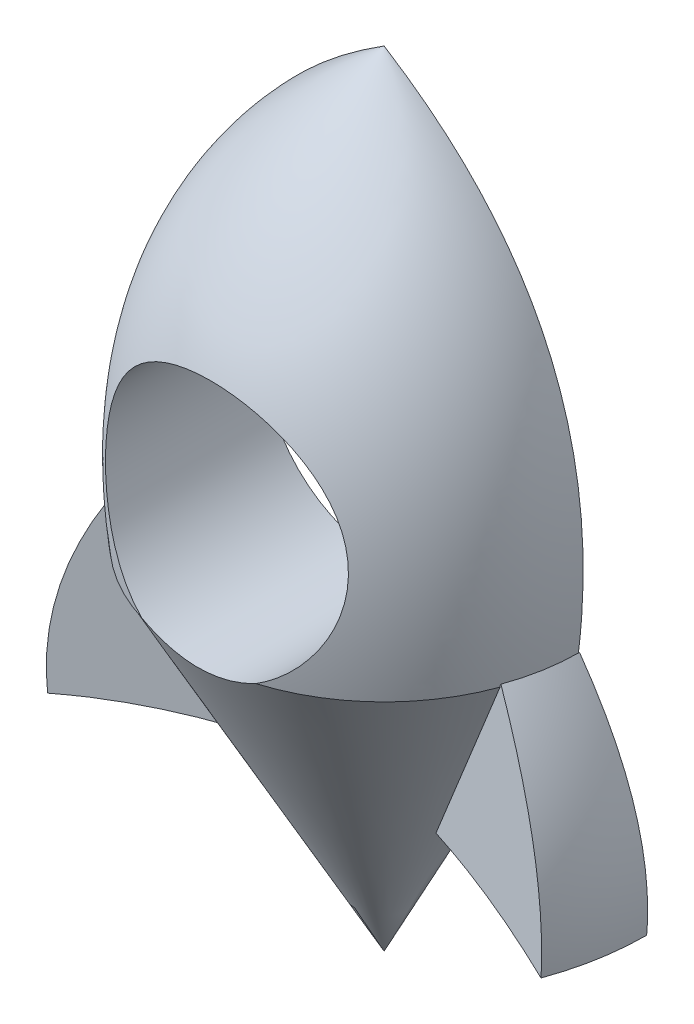
SolidWorks part; units mm, degrees
ref_plane "Front Plane" through (0, 0, 0) normal (0, 0, 1) x (1, 0, 0)
ref_plane "Top Plane" through (0, 0, 0) normal (0, 1, 0) x (1, 0, 0)
ref_plane "Right Plane" through (0, 0, 0) normal (1, 0, 0) x (0, 0, -1)
sketch "Sketch1" plane through (0, 0, 0) normal (0, 0, 1) x (1, 0, 0)
  line L0 (41.2575, 134.337) -> (163.2575, 134.337) construction
  line L1 (37.0343, 1.5646) -> (18.4311, 35.4141)
  line L4 (37.0343, 1.5646) -> (37.0343, 34.0429)
  line L5 (37.0343, 57.2579) -> (37.0343, 76.7324)
  arc A0 (37.0343, 57.2579) -> (37.0343, 34.0429) centre (37.0343, 45.6504) ccw
  spline S0 degree 2 poles (18.4311, 35.4141) (14.8948, 62.9056) (37.0343, 76.7324) knots 0 0 0 1 1 1
revolve "Revolve1" add sketch "Sketch1" angle 180 about L5
sketch "Sketch2" plane through (0, 0, 0) normal (0, 0, -1) x (-1, 0, 0)
  circle A0 centre (-37.0343, 45.6504) radius 11.6075
extrude "Cut-Extrude1" cut sketch "Sketch2" against normal blind 30
sketch "Sketch3" plane through (0, 0, 0) normal (0, 0, -1) x (-1, 0, 0)
  line L0 (-55.7749, 35.7487) -> (-45.3066, 16.701)
  line L1 (-37.0343, 76.7324) -> (-37.0343, 1.5646) construction
  line L2 (-18.2936, 35.7487) -> (-28.762, 16.701)
  spline S0 degree 2 poles (-45.3066, 16.701) (-54.0698, 17.2628) (-62.2069, 15.4708) knots 0 0 0 0.385925 0.385925 0.385925
  spline S1 degree 2 poles (-55.7749, 35.7487) (-63.0997, 25.4371) (-62.2069, 15.4708) knots 0 0 0 0.56509 0.56509 0.56509
  spline S2 degree 2 poles (-18.2936, 35.7487) (-10.9689, 25.4371) (-11.8616, 15.4708) knots 0 0 0 0.56509 0.56509 0.56509
  spline S3 degree 2 poles (-28.762, 16.701) (-19.9987, 17.2628) (-11.8616, 15.4708) knots 0 0 0 0.385925 0.385925 0.385925
revolve "Revolve3" add sketch "Sketch3" angle 20 about L1 other way angle 20
sketch "Sketch6" plane through (0, 0, 0) normal (0, 0, -1) x (-1, 0, 0)
  line L1 (6.0854, -13.3872) -> (-81.6103, -13.3872)
  line L2 (6.0854, -13.3872) -> (6.0854, 97.4006)
  line L3 (6.0854, 97.4006) -> (-81.6103, 97.4006)
  line L4 (-81.6103, -13.3872) -> (-81.6103, 97.4006)
extrude "Cut-Extrude2" cut sketch "Sketch6" along normal blind 30
